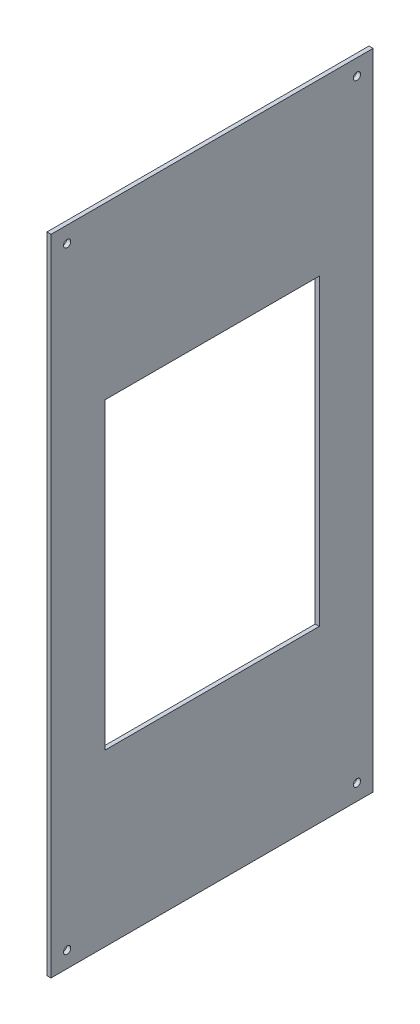
SolidWorks part; units mm, degrees
ref_plane "Front Plane" through (0, 0, 0) normal (1, 0, 0) x (0, 1, 0)
ref_plane "Top Plane" through (0, 0, 0) normal (0, 0, 1) x (0, 1, 0)
ref_plane "Right Plane" through (0, 0, 0) normal (0, 1, 0) x (-1, 0, 0)
sketch "Sketch1" plane through (0, 0, 0) normal (1, 0, 0) x (0, 1, 0)
  line L0 (0, 0) -> (0, 125) construction
  line L1 (-250, -125) -> (250, -125)
  line L2 (-250, -125) -> (-250, 125)
  line L3 (-250, 125) -> (250, 125)
  line L4 (250, -125) -> (250, 125)
  line L5 (-250, -125) -> (250, 125) construction
  line L6 (-250, 125) -> (250, -125) construction
  line L7 (0, 0) -> (250, 0) construction
  circle A0 centre (-237.5, 112.5) radius 2.8
  circle A1 centre (237.5, 112.5) radius 2.8
  circle A2 centre (237.5, -112.5) radius 2.8
  circle A3 centre (-237.5, -112.5) radius 2.8
  point P0 (0, 0)
  dimension "D3" = 5.6
  dimension "D1" = 500
  dimension "D2" = 250
  dimension "D4" = 12.5
  dimension "D5" = 12.5
extrude "Boss-Extrude1" add sketch "Sketch1" along normal blind 3.175
sketch "Sketch2" plane through (3.175, 0, 0) normal (1, 0, 0) x (0, 1, 0)
  line L1 (117.75, -83.25) -> (-117.75, -83.25)
  line L2 (117.75, -83.25) -> (117.75, 83.25)
  line L3 (117.75, 83.25) -> (-117.75, 83.25)
  line L4 (-117.75, -83.25) -> (-117.75, 83.25)
  line L5 (117.75, -83.25) -> (-117.75, 83.25) construction
  line L6 (117.75, 83.25) -> (-117.75, -83.25) construction
  point P0 (0, 0)
  dimension "D1" = 235.5
  dimension "D2" = 166.5
extrude "Cut-Extrude1" cut sketch "Sketch2" against normal through all
